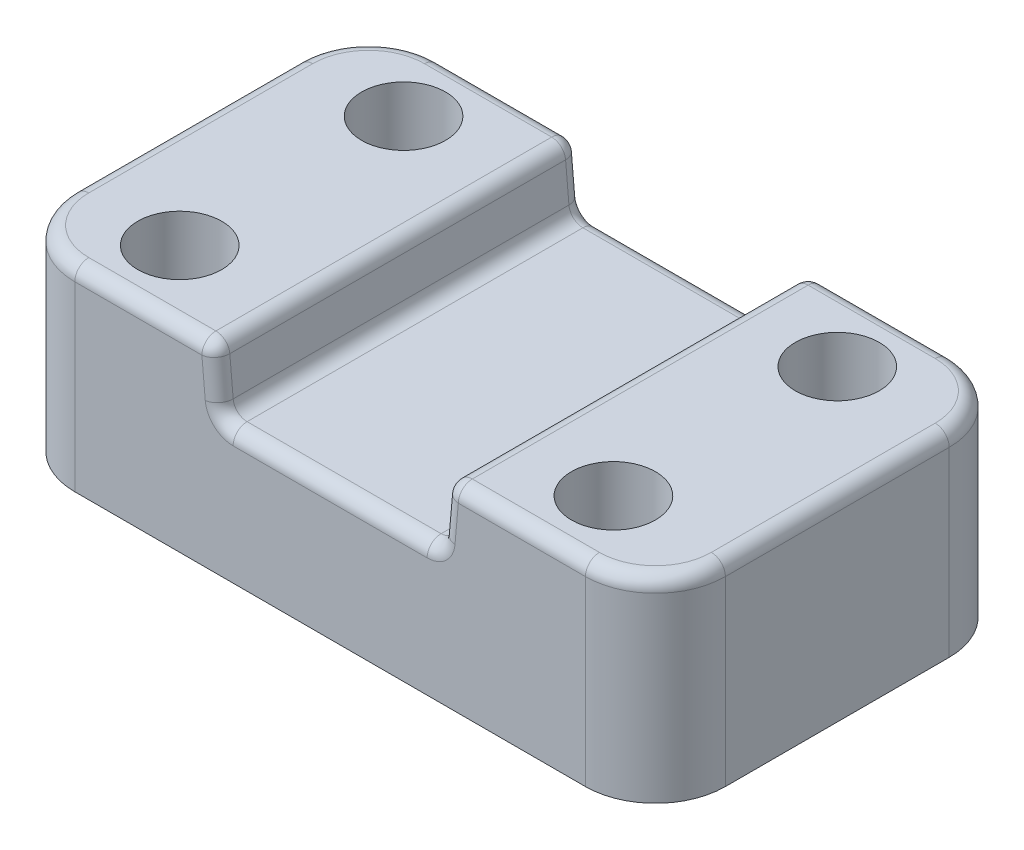
SolidWorks part; units mm, degrees
material "6061 Alloy"
ref_plane "Front Plane" through (0, 0, 0) normal (0, 0, 1) x (1, 0, 0)
ref_plane "Top Plane" through (0, 0, 0) normal (0, 1, 0) x (1, 0, 0)
ref_plane "Right Plane" through (0, 0, 0) normal (1, 0, 0) x (0, 0, -1)
sketch "Sketch2" plane through (0, 0, 0) normal (0, 1, 0) x (1, 0, 0)
  line L0 (-15.75, 8) -> (15.25, 8) construction
  line L1 (23.25, -13) -> (-23.25, -13)
  line L2 (23.25, -13) -> (23.25, 13)
  line L3 (23.25, 13) -> (-23.25, 13)
  line L4 (-23.25, -13) -> (-23.25, 13)
  line L5 (23.25, -13) -> (-23.25, 13) construction
  line L6 (23.25, 13) -> (-23.25, -13) construction
  line L7 (-23.25, 0) -> (23.25, 0) construction
  circle A0 centre (-15.75, 8) radius 2.6423 construction
  circle A1 centre (15.25, 8) radius 2.6682 construction
  circle A2 centre (15.25, -8) radius 2.6682 construction
  circle A3 centre (-15.75, -8) radius 2.6423 construction
  point P0 (0, 0)
  point P17 (-15.75, -8)
  point P18 (-15.75, 8)
  point P19 (15.25, 8)
  point P20 (15.25, -8)
  dimension "D4" = 7.5
  dimension "D5" = 8
  dimension "D6" = 5
  dimension "D1" = 26
  dimension "D2" = 46.5
  dimension "D3" = 31
extrude "Boss-Extrude1" add sketch "Sketch2" along normal blind 14
ref_plane "Plane1" through (0, 0, 15.5) normal (0, 0, 1) x (1, 0, 0)
sketch "Sketch5" plane through (0, 0, 15.5) normal (0, 0, 1) x (1, 0, 0)
  line L0 (-8.25, 14) -> (-7.8482, 9.5)
  line L1 (-7, 0) -> (7, 0)
  line L2 (7.8482, 9.5) -> (8.25, 14)
  line L3 (8.25, 14) -> (-8.25, 14)
  line L4 (-23.25, 0) -> (23.25, 0)
  line L5 (23.25, 0) -> (23.25, 14)
  line L6 (23.25, 14) -> (-23.25, 14)
  line L7 (-23.25, 14) -> (-23.25, 0)
  line L8 (-23.25, 0) -> (23.25, 0)
  line L9 (23.25, 0) -> (23.25, 14)
  line L10 (23.25, 14) -> (-23.25, 14)
  line L11 (-23.25, 14) -> (-23.25, 0)
  line L12 (0, 9.5) -> (0, 14) construction
  line L13 (-7.8482, 9.5) -> (7.8482, 9.5)
  dimension "D2" = 15
  dimension "D3" = 15
  dimension "D4" = 14
  dimension "D5" = 9.5
  dimension "D1" = 0
extrude "Cut-Extrude1" cut sketch "Sketch5" against normal through all contours L13 L2 L3 L0
fillet "Fillet1" radius 5 4 edges at (23.25, 7, -13) (23.25, 7, 13) (-23.25, 7, -13) (-23.25, 7, 13)
fillet "Fillet2" radius 1 20 edges at (-8.0491, 11.75, -13) (-8.0491, 11.75, 13) (8.0491, 11.75, -13) (8.0491, 11.75, 13) (13.25, 14, -13) (21.7855, 14, -11.5355) (23.25, 14, 0) (21.7855, 14, 11.5355) (-13.25, 14, -13) (-21.7855, 14, -11.5355) (-13.25, 14, 13) (-21.7855, 14, 11.5355) (-7.8482, 9.5, 0) (-8.25, 14, 0) (7.8482, 9.5, 0) (8.25, 14, 0) (13.25, 14, 13) (0, 9.5, -13) (0, 9.5, 13) (-23.25, 14, 0)
sketch "Sketch6" plane through (0, 14, 0) normal (0, 1, 0) x (1, 0, 0)
  point P0 (15.25, 8)
  point P2 (15.25, -8)
  point P4 (-15.75, -8)
  point P6 (-15.75, 8)
hole_wizard "Ø6.0mm Dowel Hole1" positions "Sketch6" profile "Sketch7" hole size "Ø6.0" standard "ANSI Metric" end condition through all
sketch "Sketch7" plane through (15.25, 14, -8) normal (1, 0, 0) x (0, 0, 1)
  line L0 (0, 0) -> (0, 14)
  line L1 (0, 14) -> (3, 14)
  line L2 (3, 14) -> (3, 0)
  line L5 (3, 0) -> (0, 0)
  line L11 (0, -6.35) -> (0, 107.95) construction
  dimension "Thru Hole Dia." = 6
  dimension "Thru Hole Depth" = 14
